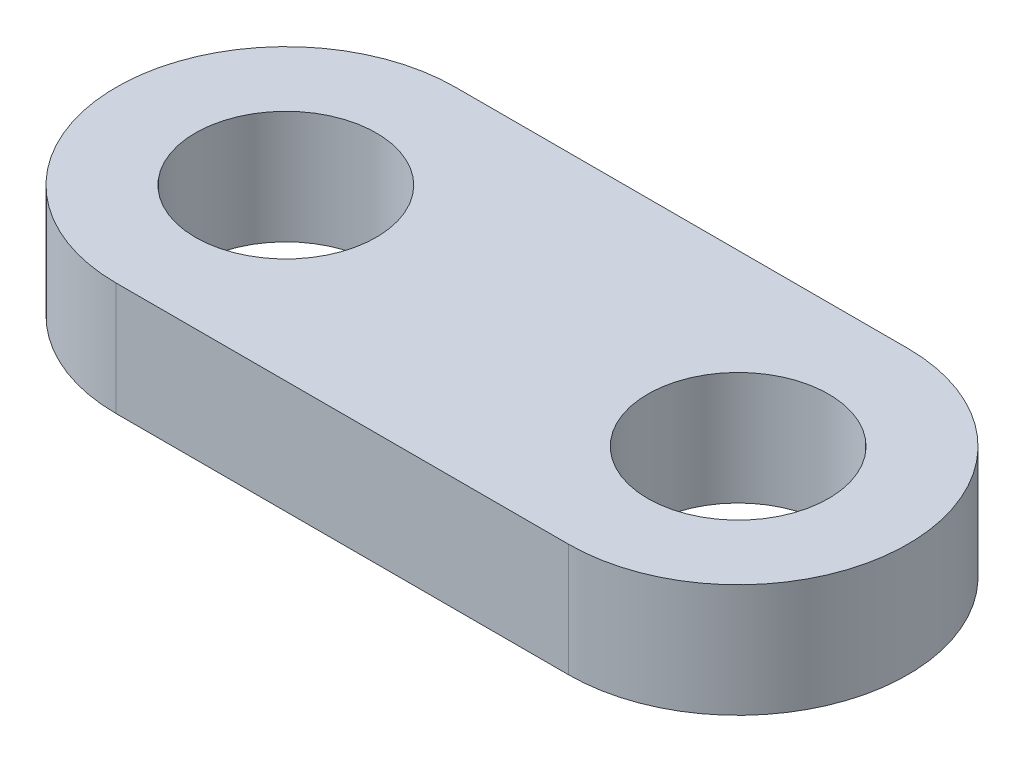
SolidWorks part; units mm, degrees
ref_plane "Front Plane" through (0, 0, 0) normal (0, 0, 1) x (1, 0, 0)
ref_plane "Top Plane" through (0, 0, 0) normal (0, 1, 0) x (1, 0, 0)
ref_plane "Right Plane" through (0, 0, 0) normal (1, 0, 0) x (0, 0, -1)
sketch "Sketch1" plane through (0, 0, 0) normal (0, 1, 0) x (1, 0, 0)
  line L1 (-10, -7.5) -> (10, -7.5)
  line L2 (-10, -7.5) -> (-10, 7.5) construction
  line L3 (-10, 7.5) -> (10, 7.5)
  line L4 (10, -7.5) -> (10, 7.5) construction
  line L5 (-10, -7.5) -> (10, 7.5) construction
  line L6 (-10, 7.5) -> (10, -7.5) construction
  arc A0 (-10, 7.5) -> (-10, -7.5) centre (-10, 0) ccw
  arc A1 (10, 7.5) -> (10, -7.5) centre (10, 0) cw
  circle A2 centre (-10, 0) radius 4
  circle A3 centre (10, 0) radius 4
  point P0 (0, 0)
  dimension "D3" = 8
  dimension "D1" = 20
  dimension "D2" = 15
extrude "Boss-Extrude1" add sketch "Sketch1" along normal blind 5
